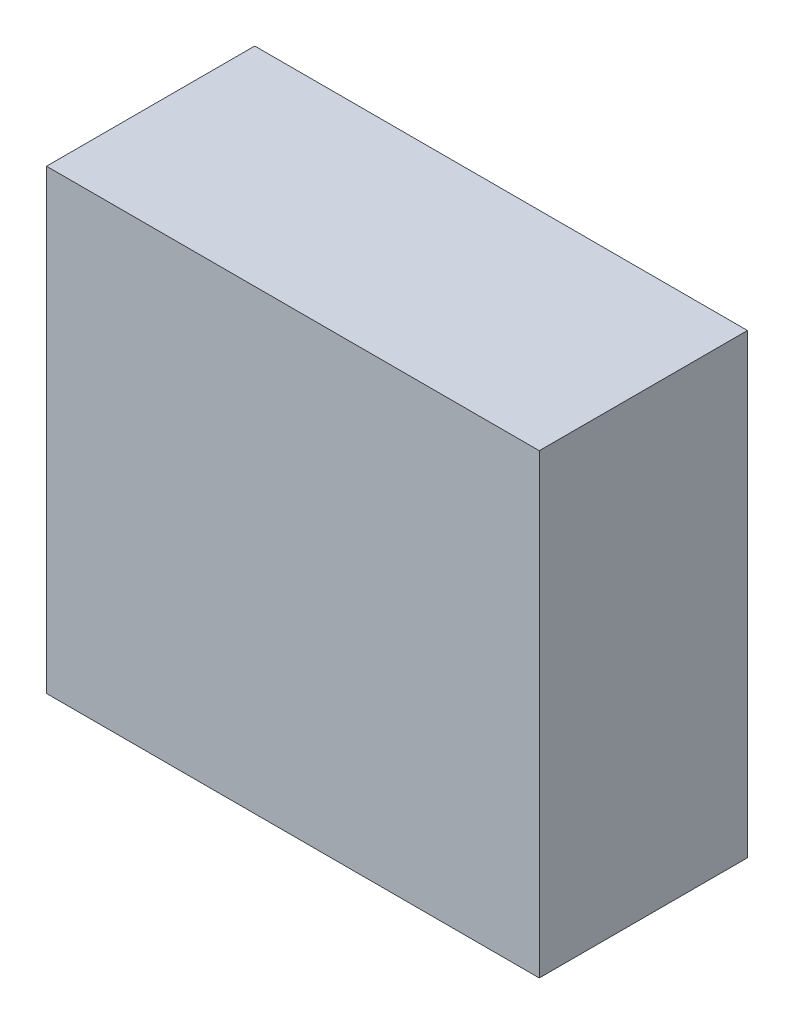
SolidWorks part; units mm, degrees
material "Massless"
ref_plane "Front Plane" through (0, 0, 0) normal (0, 0, 1) x (1, 0, 0)
ref_plane "Top Plane" through (0, 0, 0) normal (0, 1, 0) x (1, 0, 0)
ref_plane "Right Plane" through (0, 0, 0) normal (1, 0, 0) x (0, 0, -1)
sketch "Sketch2" plane through (0, 0, 0) normal (0, 1, 0) x (1, 0, 0)
  line L1 (0, 0) -> (180.34, 0)
  line L2 (0, 0) -> (0, 76.2)
  line L3 (0, 76.2) -> (180.34, 76.2)
  line L4 (180.34, 0) -> (180.34, 76.2)
  dimension "D1" = 180.34
  dimension "D2" = 76.2
extrude "Boss-Extrude1" add sketch "Sketch2" along normal blind 167.132
